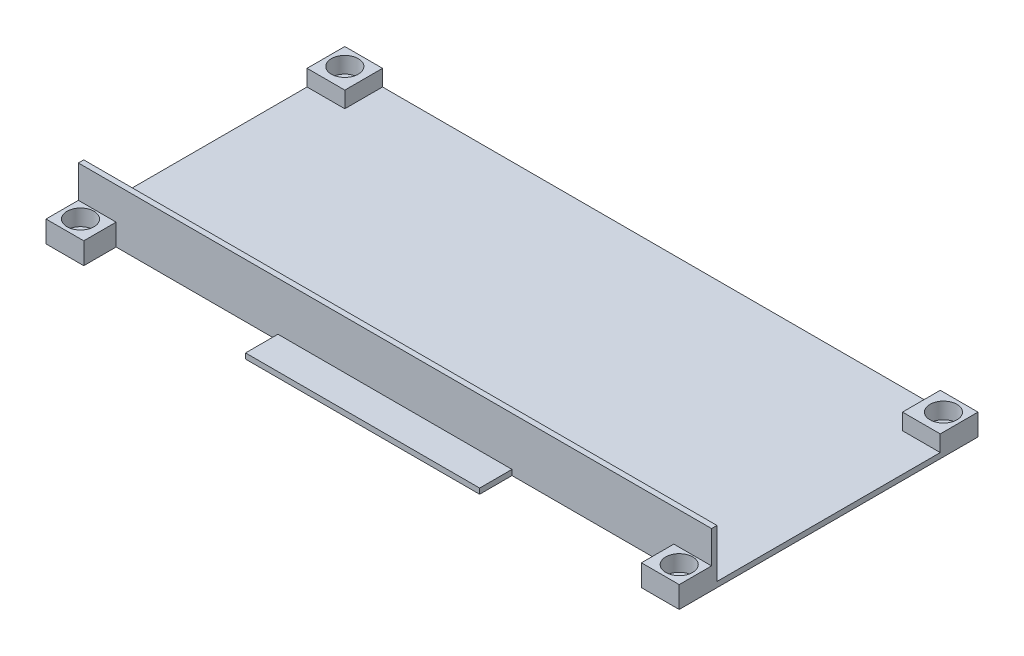
SolidWorks part; units mm, degrees
ref_plane "Front Plane" through (0, 0, 0) normal (0, 0, 1) x (1, 0, 0)
ref_plane "Top Plane" through (0, 0, 0) normal (0, 1, 0) x (1, 0, 0)
ref_plane "Right Plane" through (0, 0, 0) normal (1, 0, 0) x (0, 0, -1)
sketch "Sketch1" plane through (0, 0, 0) normal (0, 1, 0) x (1, 0, 0)
  line L1 (-58.7, -27.7) -> (58.7, -27.7)
  line L2 (-58.7, -27.7) -> (-58.7, 27.7)
  line L3 (-58.7, 27.7) -> (58.7, 27.7)
  line L4 (58.7, -27.7) -> (58.7, 27.7)
  line L5 (-58.7, -27.7) -> (58.7, 27.7) construction
  line L6 (-58.7, 27.7) -> (58.7, -27.7) construction
  point P0 (0, 0)
  dimension "D1" = 55.4
  dimension "D2" = 117.4
extrude "Boss-Extrude1" add sketch "Sketch1" along normal blind 1
sketch "Sketch2" plane through (0, 1, 0) normal (0, 1, 0) x (1, 0, 0)
  line L0 (0, 27.7) -> (0, -27.7) construction
  line L1 (58.7, 27.7) -> (-58.7, 27.7) construction
  line L2 (-58.7, -27.7) -> (58.7, -27.7) construction
  line L3 (-58.7, 0) -> (58.7, 0) construction
  line L4 (-58.7, 27.7) -> (-58.7, -27.7) construction
  line L5 (58.7, -27.7) -> (58.7, 27.7) construction
  line L6 (58.7, 20.7) -> (51.7, 20.7)
  line L7 (-58.7, 27.7) -> (-51.7, 27.7)
  line L8 (-58.7, 27.7) -> (-58.7, 20.7)
  line L9 (-58.7, 20.7) -> (-51.7, 20.7)
  line L10 (-51.7, 27.7) -> (-51.7, 20.7)
  line L11 (51.7, 27.7) -> (51.7, 20.7)
  line L12 (58.7, 27.7) -> (51.7, 27.7)
  line L13 (58.7, 27.7) -> (58.7, 20.7)
  line L14 (58.7, -27.7) -> (58.7, -20.7)
  line L15 (58.7, -27.7) -> (51.7, -27.7)
  line L16 (51.7, -27.7) -> (51.7, -20.7)
  line L17 (58.7, -20.7) -> (51.7, -20.7)
  line L18 (-58.7, -20.7) -> (-51.7, -20.7)
  line L19 (-51.7, -27.7) -> (-51.7, -20.7)
  line L20 (-58.7, -27.7) -> (-51.7, -27.7)
  line L21 (-58.7, -27.7) -> (-58.7, -20.7)
  dimension "D1" = 7
extrude "Boss-Extrude2" add sketch "Sketch2" along normal blind 3
sketch "Sketch3" plane through (0, 4, 0) normal (0, 1, 0) x (1, 0, 0)
  line L1 (-55.5, -24.5) -> (55.5, -24.5) construction
  line L2 (-55.5, -24.5) -> (-55.5, 24.5) construction
  line L3 (-55.5, 24.5) -> (55.5, 24.5) construction
  line L4 (55.5, -24.5) -> (55.5, 24.5) construction
  line L5 (-55.5, -24.5) -> (55.5, 24.5) construction
  line L6 (-55.5, 24.5) -> (55.5, -24.5) construction
  circle A0 centre (-55.5, 24.5) radius 1.35
  circle A1 centre (55.5, 24.5) radius 1.35
  circle A2 centre (55.5, -24.5) radius 1.35
  circle A3 centre (-55.5, -24.5) radius 1.35
  point P0 (0, 0)
  dimension "D3" = 2.7
  dimension "D1" = 49
  dimension "D2" = 111
extrude "Cut-Extrude1" cut sketch "Sketch3" against normal through all
sketch "Sketch7" plane through (0, 0, 0) normal (0, -1, 0) x (1, 0, 0)
  line L0 (0, 0) -> (0, 27.7) construction
  line L1 (51.7, 27.7) -> (21.7, 27.7)
  line L2 (51.7, 27.7) -> (51.7, 21.7)
  line L3 (51.7, 21.7) -> (21.7, 21.7)
  line L4 (21.7, 27.7) -> (21.7, 21.7)
  line L5 (-58.7, 27.7) -> (58.7, 27.7) construction
  line L6 (-21.7, 27.7) -> (-21.7, 21.7)
  line L7 (-51.7, 21.7) -> (-21.7, 21.7)
  line L8 (-51.7, 27.7) -> (-51.7, 21.7)
  line L9 (-51.7, 27.7) -> (-21.7, 27.7)
  dimension "D1" = 30
  dimension "D2" = 6
extrude "Cut-Extrude5" cut sketch "Sketch7" against normal through all
sketch "Sketch9" plane through (0, 4, 0) normal (0, 1, 0) x (1, 0, 0)
  circle A0 centre (-55.5, 24.5) radius 2.5
  circle A1 centre (55.5, 24.5) radius 2.5
  circle A2 centre (55.5, -24.5) radius 2.5
  circle A3 centre (-55.5, -24.5) radius 2.5
  dimension "D1" = 5
extrude "Cut-Extrude6" cut sketch "Sketch9" against normal offset from surface (3 mm away) 1 up to face at (0, 0, 16.4667)
sketch "Sketch10" plane through (0, 1, 0) normal (0, 1, 0) x (1, 0, 0)
  line L0 (58.7, -20.7) -> (58.7, 20.7) construction
  line L1 (58.7, -21.7) -> (-58.7, -21.7)
  line L2 (58.7, -21.7) -> (58.7, -20.7)
  line L3 (58.7, -20.7) -> (-58.7, -20.7)
  line L4 (-58.7, -21.7) -> (-58.7, -20.7)
  line L5 (-58.7, 20.7) -> (-58.7, -20.7) construction
  line L7 (-21.7, -27.7) -> (21.7, -27.7) construction
  dimension "D1" = 1
  dimension "D2" = 6
extrude "Boss-Extrude3" add sketch "Sketch10" along normal blind 9
